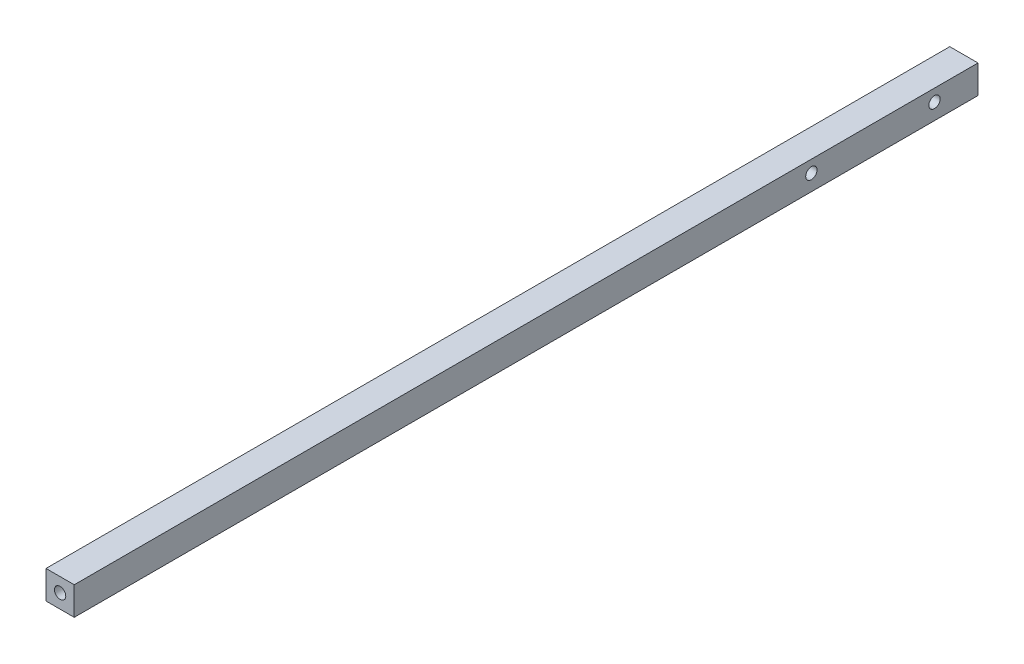
SolidWorks part; units mm, degrees
ref_plane "Plan de face" through (0, 0, 0) normal (0, 0, 1) x (1, 0, 0)
ref_plane "Plan de dessus" through (0, 0, 0) normal (0, 1, 0) x (1, 0, 0)
ref_plane "Plan de droite" through (0, 0, 0) normal (1, 0, 0) x (0, 0, -1)
sketch "Esquisse1" plane through (0, 0, 0) normal (0, 0, 1) x (1, 0, 0)
  line L1 (0, 0) -> (10, 0)
  line L2 (0, 0) -> (0, 10)
  line L3 (0, 10) -> (10, 10)
  line L4 (10, 0) -> (10, 10)
  dimension "D1" = 10
  dimension "D2" = 10
extrude "Boss.-Extru.1" add sketch "Esquisse1" along normal blind 320
sketch "Esquisse2" plane through (0, 0, 0) normal (-1, 0, 0) x (0, 0, 1)
  line L0 (63.827, 5.7) -> (-7.5908, 5.7) construction
  line L1 (320, 0) -> (0, 0) construction
  line L2 (0, 10) -> (0, 0) construction
  circle A0 centre (15.4, 5.7) radius 2
  circle A1 centre (59, 5.7) radius 2
  dimension "D4" = 4
  dimension "D5" = 4
  dimension "D1" = 5.7
  dimension "D2" = 15.4
  dimension "D3" = 43.6
extrude "Enlèv. mat.-Extru.1" cut sketch "Esquisse2" against normal through all
sketch "Esquisse3" plane through (0, 0, 0) normal (0, 0, -1) x (-1, 0, 0)
  line L0 (0, 10) -> (0, 0) construction
  line L2 (0, 0) -> (-10, 0) construction
  circle A0 centre (-5, 5) radius 2
  dimension "D1" = 4
  dimension "D2" = 5
  dimension "D3" = 5
extrude "Enlèv. mat.-Extru.2" cut sketch "Esquisse3" against normal blind 6
sketch "Esquisse4" plane through (0, 0, 320) normal (0, 0, 1) x (1, 0, 0)
  line L0 (0, 10) -> (0, 0) construction
  line L1 (0, 0) -> (10, 0) construction
  circle A0 centre (5, 5) radius 2
  dimension "D1" = 4
  dimension "D2" = 5
  dimension "D3" = 5
extrude "Enlèv. mat.-Extru.3" cut sketch "Esquisse4" against normal blind 6
